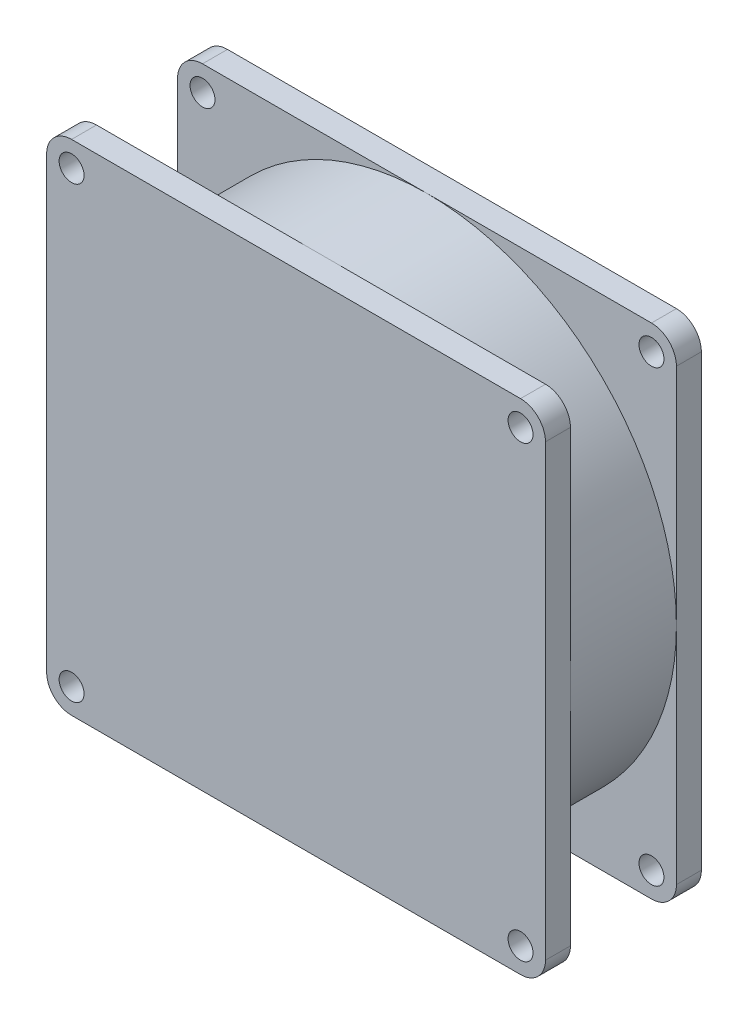
SolidWorks part; units mm, degrees
ref_plane "Front Plane" through (0, 0, 0) normal (0, 0, 1) x (1, 0, 0)
ref_plane "Top Plane" through (0, 0, 0) normal (0, 1, 0) x (1, 0, 0)
ref_plane "Right Plane" through (0, 0, 0) normal (1, 0, 0) x (0, 0, -1)
sketch "Sketch1" plane through (0, 0, 0) normal (0, 0, 1) x (1, 0, 0)
  line L1 (0, 0) -> (80, 0)
  line L2 (0, 0) -> (0, 80)
  line L3 (0, 80) -> (80, 80)
  line L4 (80, 0) -> (80, 80)
  dimension "D1" = 80
  dimension "D2" = 80
extrude "Boss-Extrude1" add sketch "Sketch1" along normal blind 4 contours L4 L3 L2 L1
fillet "Fillet2" radius 4 4 edges at (0, 80, 2) (0, 0, 2) (80, 0, 2) (80, 80, 2)
sketch "Sketch3" plane through (0, 0, 4) normal (0, 0, 1) x (1, 0, 0)
  line L0 (0, 4) -> (0, 76) construction
  line L2 (4, 0) -> (76, 0) construction
  circle A0 centre (40, 40) radius 40
  point P6 (64.7379, 2.0682)
  dimension "D1" = 80
  dimension "D2" = 40
  dimension "D3" = 40
extrude "Boss-Extrude2" add sketch "Sketch3" along normal blind 17
sketch "Sketch4" plane through (0, 0, 21) normal (0, 0, 1) x (1, 0, 0)
  line L1 (0, 0) -> (80, 0)
  line L2 (0, 0) -> (0, 80)
  line L3 (0, 80) -> (80, 80)
  line L4 (80, 0) -> (80, 80)
extrude "Boss-Extrude3" add sketch "Sketch4" along normal blind 4
fillet "Fillet3" radius 4 4 edges at (80, 0, 23) (80, 80, 23) (0, 0, 23) (0, 80, 23)
hole_wizard "Ø4.0mm Dowel Hole1" positions "Sketch5" profile "Sketch7" hole size "Ø4.0" standard "ANSI Metric" end condition through all
sketch "Sketch5" plane through (0, 0, 0) normal (0, 0, -1) x (-1, 0, 0)
  point P0 (-76, 76)
  point P3 (-4, 76)
  point P6 (-4, 4)
  point P9 (-76, 4)
sketch "Sketch7" plane through (76, 76, 0) normal (1, 0, 0) x (0, 1, 0)
  line L0 (0, 0) -> (0, 25)
  line L1 (0, 25) -> (2, 25)
  line L2 (2, 25) -> (2, 0)
  line L5 (2, 0) -> (0, 0)
  line L11 (0, -6.35) -> (0, 107.95) construction
  dimension "Thru Hole Dia." = 4
  dimension "Thru Hole Depth" = 25
